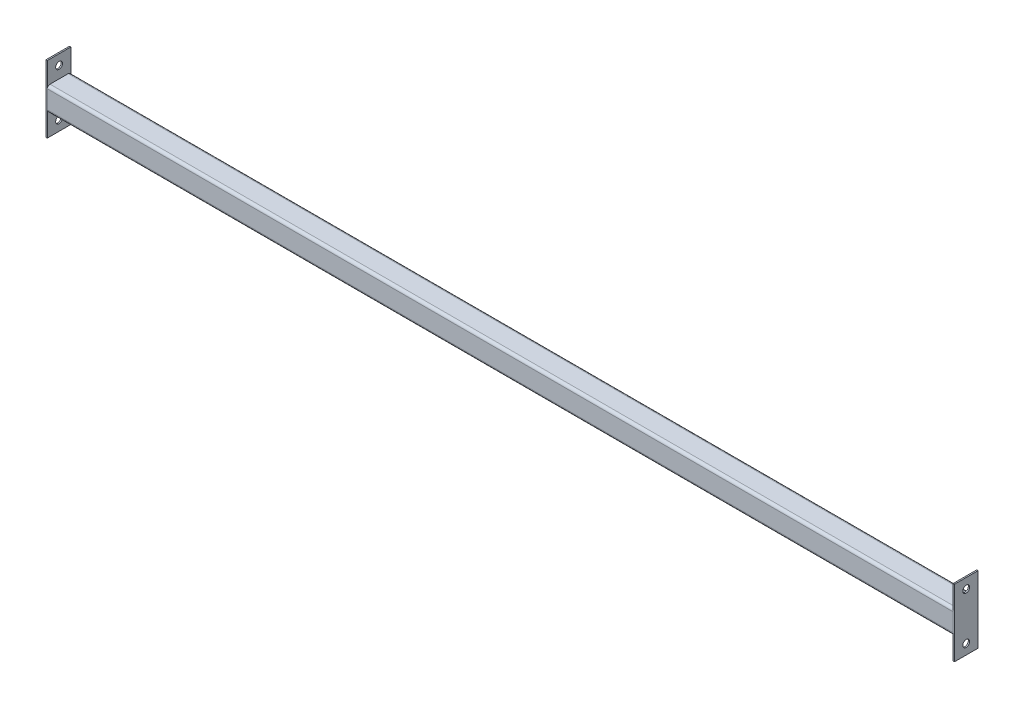
SolidWorks part; units mm, degrees
other "DetailItem1"
other "DetailItem2"
other "Weld Folder"
other "Weld Bead2"
other "Weld Bead1"
ref_plane "Front Plane" through (0, 0, 0) normal (0, 0, 1) x (1, 0, 0)
ref_plane "Top Plane" through (0, 0, 0) normal (0, 1, 0) x (1, 0, 0)
ref_plane "Right Plane" through (0, 0, 0) normal (1, 0, 0) x (0, 0, -1)
sketch3d "3DSketch1"
  line L0 (0, 0, 0) -> (0, 100, 0)
  line L1 (0, 50, 0) -> (1350, 50, 0)
  line L2 (1350, 100, 0) -> (1350, 0, 0)
  point P8 (1350, 50, 0)
  dimension "D1" = 1350
  dimension "D2" = 100
other "Square tube - configured 20 X 20 X 2(1)"
ref_plane "Plane1" through (0, 0, 0) normal (0, 1, 0) x (1, 0, 0)
sketch "Sketch1" plane through (0, 0, 0) normal (0, 1, 0) x (1, 0, 0)
  line L9 (1, -17.5) -> (-1, -17.5)
  line L10 (1, -17.5) -> (1, 17.5)
  line L11 (1, 17.5) -> (-1, 17.5)
  line L12 (-1, -17.5) -> (-1, 17.5)
  point P1 (10, 0)
  point P2 (0, 10)
  point P3 (0, -10)
  point P4 (0, 0)
  point P33 (0, 0)
  point P35 (0, 0)
  dimension "D2" = 35
  dimension "D3" = 2
  dimension "D1" = 17.5
other "Square tube - configured 20 X 20 X 2(3)"
ref_plane "Plane2" through (0, 50, 0) normal (1, 0, 0) x (0, 0, -1)
sketch "Sketch11" plane through (0, 50, 0) normal (1, 0, 0) x (0, 0, -1)
  line L0 (-13.5, -15.5) -> (13.5, -15.5)
  line L1 (-15.5, -13.5) -> (-15.5, 13.5)
  line L2 (13.5, 15.5) -> (-13.5, 15.5)
  line L3 (15.5, 13.5) -> (15.5, -13.5)
  line L4 (-13.5, -17.5) -> (13.5, -17.5)
  line L5 (-17.5, -13.5) -> (-17.5, 13.5)
  line L6 (13.5, 17.5) -> (-13.5, 17.5)
  line L7 (17.5, 13.5) -> (17.5, -13.5)
  arc A0 (17.5, 13.5) -> (13.5, 17.5) centre (13.5, 13.5) ccw
  arc A1 (13.5, -17.5) -> (17.5, -13.5) centre (13.5, -13.5) ccw
  arc A2 (-17.5, -13.5) -> (-13.5, -17.5) centre (-13.5, -13.5) ccw
  arc A3 (-13.5, 17.5) -> (-17.5, 13.5) centre (-13.5, 13.5) ccw
  arc A4 (-13.5, 15.5) -> (-15.5, 13.5) centre (-13.5, 13.5) ccw
  arc A5 (15.5, 13.5) -> (13.5, 15.5) centre (13.5, 13.5) ccw
  arc A6 (13.5, -15.5) -> (15.5, -13.5) centre (13.5, -13.5) ccw
  arc A7 (-15.5, -13.5) -> (-13.5, -15.5) centre (-13.5, -13.5) ccw
  point P0 (-17.5, 0)
  point P1 (17.5, 0)
  point P2 (0, 17.5)
  point P3 (0, -17.5)
  point P4 (0, 0)
  point P5 (-17.5, -17.5)
  point P6 (17.5, -17.5)
  point P7 (17.5, 17.5)
  point P8 (-17.5, 17.5)
  point P33 (0, 0)
  dimension "D1" = 4
  dimension "Thickness" = 2
  dimension "V_leg" = 35
other "Trim/Extend1"
other "Trim/Extend2"
hole_wizard "Ø10.2 (10.2) Diameter Hole1" positions "Sketch12" profile "Sketch13" hole size "Ø10.2" standard "ANSI Metric" end condition through all
sketch "Sketch12" plane through (-1, 0, 0) normal (-1, 0, 0) x (0, 0, 1)
  line L4 (-17.5, 100) -> (-17.5, 0) construction
  line L5 (0, 0) -> (0, 100) construction
  point P0 (0, 15)
  point P4 (0, 85)
  point P20 (-17.5, 50)
  dimension "D1" = 70
  dimension "D2" = 35
sketch "Sketch13" plane through (-1, 15, 0) normal (0, 1, 0) x (0, 0, 1)
  line L0 (0, 0) -> (0, 1352)
  line L1 (0, 1352) -> (5.1, 1352)
  line L2 (5.1, 1352) -> (5.1, 0)
  line L5 (5.1, 0) -> (0, 0)
  line L11 (0, -6.35) -> (0, 107.95) construction
  dimension "Thru Hole Dia." = 10.2
  dimension "Thru Hole Depth" = 1352
equation "\"D2@Sketch12\"=\"D1@Sketch12\"/2"
equation "\"D1@Sketch1\"=\"D2@Sketch1\"/2"
